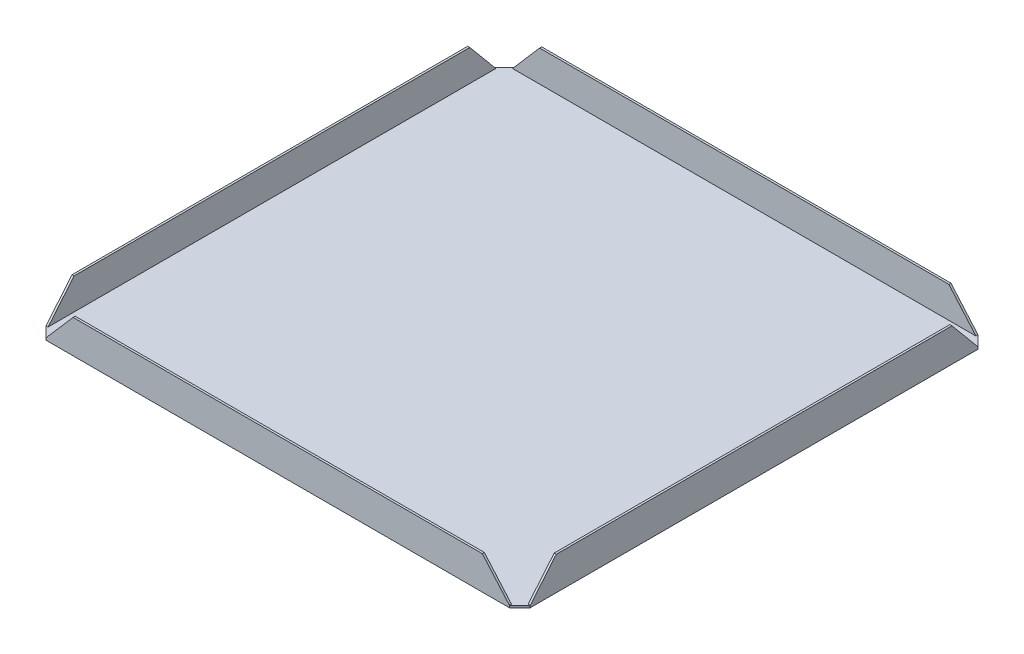
SolidWorks part; units mm, degrees
material "6061 Alloy"
ref_plane "Front Plane" through (0, 0, 0) normal (0, 0, 1) x (1, 0, 0)
ref_plane "Top Plane" through (0, 0, 0) normal (0, 1, 0) x (1, 0, 0)
ref_plane "Right Plane" through (0, 0, 0) normal (1, 0, 0) x (0, 0, -1)
sketch "Sketch1" plane through (0, 0, 0) normal (0, 1, 0) x (1, 0, 0)
  line L0 (-232.5, 215) -> (-222.5, 225)
  line L1 (-222.5, -225) -> (222.5, -225)
  line L2 (-232.5, -215) -> (-232.5, 215)
  line L3 (-222.5, 225) -> (222.5, 225)
  line L4 (232.5, -215) -> (232.5, 215)
  line L5 (-232.5, -225) -> (232.5, 225) construction
  line L6 (-232.5, 225) -> (232.5, -225) construction
  line L7 (222.5, 225) -> (232.5, 215)
  line L8 (222.5, -225) -> (232.5, -215)
  line L9 (-222.5, -225) -> (-232.5, -215)
  point P0 (0, 0)
  dimension "D1" = 465
  dimension "D2" = 450
extrude "Boss-Extrude1" add sketch "Sketch1" along normal blind 2
sketch "Sketch3" plane through (0, 0, 225) normal (0, 0, 1) x (1, 0, 0)
  line L0 (-222.5, 2) -> (222.5, 2)
  line L1 (222.5, 2) -> (196.5, 32)
  line L2 (196.5, 32) -> (-196.5, 32)
  line L3 (-196.5, 32) -> (-222.5, 2)
  line L4 (0, 2) -> (0, 50.4399) construction
  dimension "D1" = 30
  dimension "D2" = 393
extrude "Boss-Extrude2" add sketch "Sketch3" against normal blind 2
sketch "Sketch4" plane through (-232.5, 0, 0) normal (-1, 0, 0) x (0, 0, 1)
  line L0 (-215, 2) -> (215, 2)
  line L1 (215, 2) -> (190, 32)
  line L2 (190, 32) -> (-190, 32)
  line L3 (-190, 32) -> (-215, 2)
  line L4 (0, 0) -> (0, 87.9877) construction
  dimension "D1" = 30
  dimension "D2" = 380
extrude "Boss-Extrude3" add sketch "Sketch4" against normal blind 2
mirror "Mirror2" about plane through (0, 0, 0) normal (1, 0, 0) of "Boss-Extrude3"
mirror "Mirror3" about plane through (0, 0, 0) normal (0, 0, 1) of "Boss-Extrude2"
